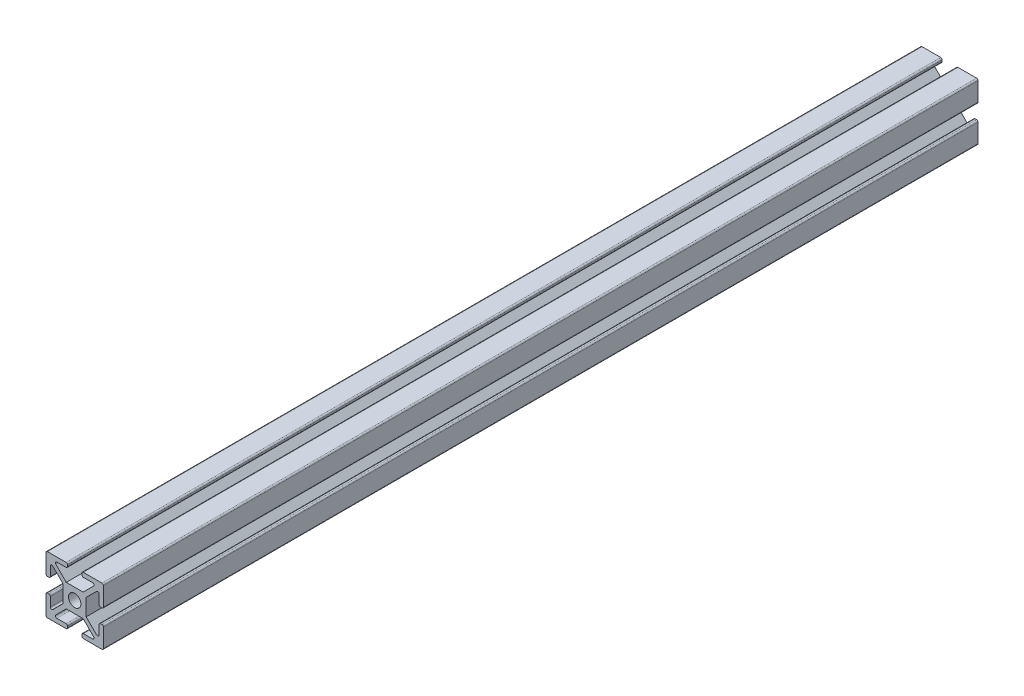
SolidWorks part; units mm, degrees
material "6061 Alloy"
ref_plane "Front Plane" through (0, 0, 0) normal (0, 0, 1) x (1, 0, 0)
ref_plane "Top Plane" through (0, 0, 0) normal (0, 1, 0) x (1, 0, 0)
ref_plane "Right Plane" through (0, 0, 0) normal (1, 0, 0) x (0, 0, -1)
sketch "Sketch1" plane through (0, 0, 0) normal (0, 0, 1) x (1, 0, 0)
  line L0 (-10, 2.5) -> (-8.5, 2.5)
  line L1 (-2.9393, 4) -> (0, 4)
  line L2 (-2.5, 10) -> (-10, 10)
  line L3 (-7.4393, 8.5) -> (-2.9393, 4)
  line L4 (-2.5, 8.5) -> (-7.4393, 8.5)
  line L5 (-8.5, 2.5) -> (-8.5, 7.4393)
  line L6 (-8.5, 7.4393) -> (-4, 2.9393)
  line L7 (-4, 2.9393) -> (-4, 0)
  line L8 (-4, 0) -> (-10, 0) construction
  line L9 (0, 10) -> (0, -10) construction
  line L10 (-10, 10) -> (0, 0) construction
  line L11 (-10, 2.5) -> (-10, 10)
  line L12 (-2.5, 10) -> (-2.5, 8.5)
  line L13 (-2.5, 10) -> (0, 10) construction
  line L14 (-10, 2.5) -> (-10, 0) construction
  line L15 (2.9393, 4) -> (0, 4)
  line L16 (4, 2.9393) -> (4, 0)
  line L17 (8.5, 7.4393) -> (4, 2.9393)
  line L18 (8.5, 2.5) -> (8.5, 7.4393)
  line L19 (10, 2.5) -> (8.5, 2.5)
  line L20 (10, 2.5) -> (10, 10)
  line L21 (2.5, 10) -> (10, 10)
  line L22 (2.5, 10) -> (2.5, 8.5)
  line L23 (2.5, 8.5) -> (7.4393, 8.5)
  line L24 (7.4393, 8.5) -> (2.9393, 4)
  line L25 (4, -2.9393) -> (4, 0)
  line L26 (2.9393, -4) -> (0, -4)
  line L27 (7.4393, -8.5) -> (2.9393, -4)
  line L28 (2.5, -8.5) -> (7.4393, -8.5)
  line L29 (2.5, -10) -> (2.5, -8.5)
  line L30 (2.5, -10) -> (10, -10)
  line L31 (10, -2.5) -> (10, -10)
  line L32 (10, -2.5) -> (8.5, -2.5)
  line L33 (8.5, -2.5) -> (8.5, -7.4393)
  line L34 (8.5, -7.4393) -> (4, -2.9393)
  line L35 (-2.9393, -4) -> (0, -4)
  line L36 (-4, -2.9393) -> (-4, 0)
  line L37 (-8.5, -7.4393) -> (-4, -2.9393)
  line L38 (-8.5, -2.5) -> (-8.5, -7.4393)
  line L39 (-10, -2.5) -> (-8.5, -2.5)
  line L40 (-10, -2.5) -> (-10, -10)
  line L41 (-2.5, -10) -> (-10, -10)
  line L42 (-2.5, -10) -> (-2.5, -8.5)
  line L43 (-2.5, -8.5) -> (-7.4393, -8.5)
  line L44 (-7.4393, -8.5) -> (-2.9393, -4)
  circle A0 centre (0, 0) radius 2.15
  point P53 (0, 0)
  dimension "D2" = 4.3
  dimension "D1" = 10
  dimension "D3" = 2.5
  dimension "D4" = 1.5
  dimension "D5" = 1.5
  dimension "D6" = 4
  dimension "D7" = 4
extrude "Boss-Extrude1" add sketch "Sketch1" along normal blind 304.8
fillet "Fillet1" radius 0.5 28 edges at (8.5, 2.5, 152.4) (2.5, 8.5, 152.4) (2.5, 10, 152.4) (2.5, -10, 152.4) (-10, 2.5, 152.4) (-8.5, -7.4393, 152.4) (-10, -10, 152.4) (-8.5, 7.4393, 152.4) (-7.4393, 8.5, 152.4) (7.4393, 8.5, 152.4) (8.5, -7.4393, 152.4) (7.4393, -8.5, 152.4) (-7.4393, -8.5, 152.4) (2.5, -8.5, 152.4) (-2.5, -10, 152.4) (-2.5, -8.5, 152.4) (10, -10, 152.4) (8.5, -2.5, 152.4) (10, -2.5, 152.4) (10, 2.5, 152.4) (-10, -2.5, 152.4) (-8.5, -2.5, 152.4) (-8.5, 2.5, 152.4) (-2.5, 8.5, 152.4) (-2.5, 10, 152.4) (-10, 10, 152.4) (10, 10, 152.4) (8.5, 7.4393, 152.4)
